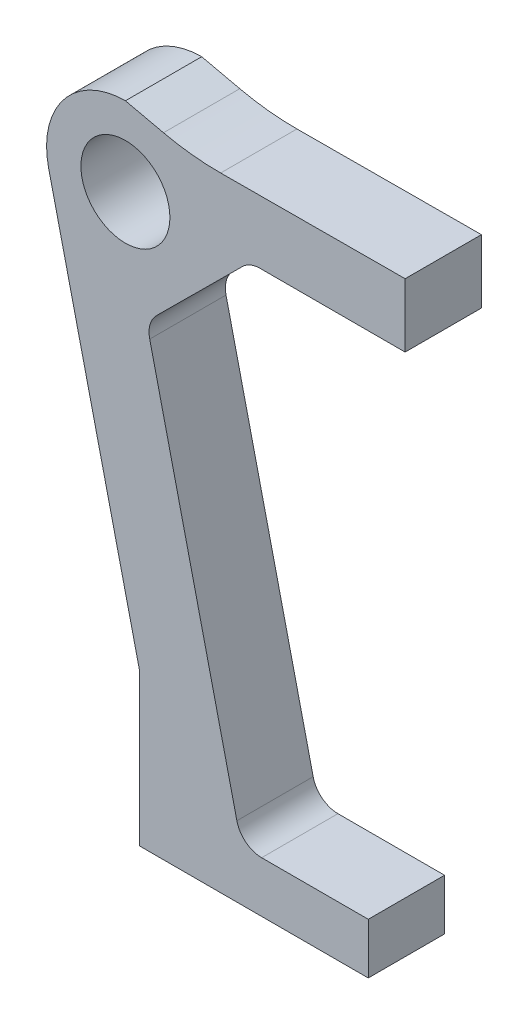
SolidWorks part; units mm, degrees
ref_plane "Plan de face" through (0, 0, 0) normal (0, 0, 1) x (1, 0, 0)
ref_plane "Plan de dessus" through (0, 0, 0) normal (0, 1, 0) x (1, 0, 0)
ref_plane "Plan de droite" through (0, 0, 0) normal (1, 0, 0) x (0, 0, -1)
sketch "Esquisse1" plane through (0, 0, 0) normal (0, 0, 1) x (1, 0, 0)
  line L0 (0.9811, 13.3706) -> (4.55, -1.925)
  line L1 (4.55, -7.925) -> (13.55, -7.925)
  line L2 (13.55, -7.925) -> (13.55, -5.925)
  line L3 (13.55, -5.925) -> (9.3574, -5.925)
  line L4 (8.3836, -5.1522) -> (4.9562, 9.5368)
  line L6 (15, 16.6156) -> (15, 14.1156)
  line L8 (4.55, -1.925) -> (4.55, -7.925)
  line L9 (11.55, 10.2) -> (11.55, -10.2) construction
  line L10 (5.225, 10.4732) -> (8.596, 13.8248)
  line L11 (10, -12.5) -> (10, 17.5) construction
  line L12 (15, 14.1156) -> (9.3011, 14.1156)
  line L13 (11.5429, 15.9784) -> (16.5429, 15.9971) construction
  line L14 (11.5429, 15.9784) -> (16.5429, 15.9971) construction
  line L15 (4, 17.175) -> (5.4979, 16.8356)
  line L16 (15, 16.6156) -> (7.7455, 16.5884)
  arc A3 (4, 17.175) -> (0.9811, 13.3706) centre (4, 14.075) ccw
  arc A4 (9.3574, -5.925) -> (8.3836, -5.1522) centre (9.3574, -4.925) cw
  arc A6 (9.3011, 14.1156) -> (8.596, 13.8248) centre (9.3011, 13.1156) ccw
  arc A7 (4.9562, 9.5368) -> (5.225, 10.4732) centre (5.93, 9.7641) cw
  circle A8 centre (4, 14.075) radius 1.75
  arc A9 (7.7455, 16.5884) -> (5.4979, 16.8356) centre (7.708, 26.5883) cw
  point P17 (4, 10.975)
  dimension "D2" = 6.2
  dimension "D5" = 6
  dimension "D6" = 1
  dimension "D14" = 0.5
  dimension "D4" = 1
  dimension "D13" = 3.5
  dimension "D15" = 10
  dimension "D3" = 2.5
  dimension "D7" = 2
  dimension "D8" = 2
  dimension "D9" = 9
  dimension "D10" = 5
  dimension "D11" = 19
  dimension "D12" = 3
extrude "Boss.-Extru.1" add sketch "Esquisse1" along normal blind 3 from offset 0.2
